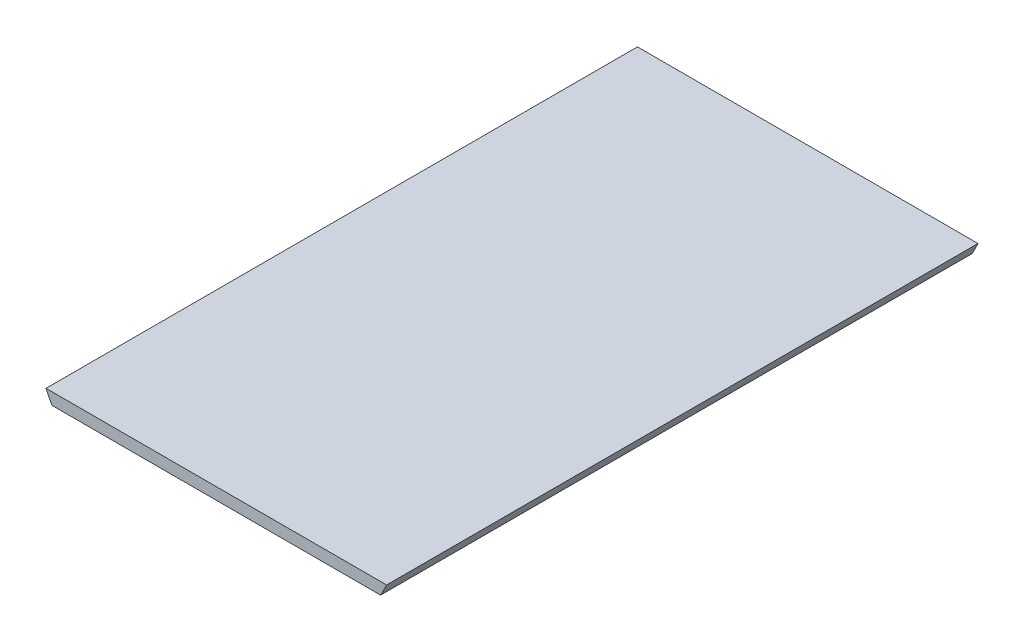
SolidWorks part; units mm, degrees
material "Brass"
ref_plane "Front Plane" through (0, 0, 0) normal (0, 0, 1) x (1, 0, 0)
ref_plane "Top Plane" through (0, 0, 0) normal (0, 1, 0) x (1, 0, 0)
ref_plane "Right Plane" through (0, 0, 0) normal (1, 0, 0) x (0, 0, -1)
sketch "Sketch2" plane through (0, 0, 0) normal (0, 0, 1) x (1, 0, 0)
  line L1 (0, -21.393) -> (0, -24.5934) construction
  line L2 (-44.45, -24.5934) -> (44.45, -24.5934)
  line L4 (-46.0758, -21.393) -> (46.0758, -21.393)
  arc A1 (-46.0758, -21.393) -> (-44.45, -24.5934) centre (0, 0) ccw
  arc A3 (44.45, -24.5934) -> (46.0758, -21.393) centre (0, 0) ccw
  dimension "D2" = 3.2004
extrude "Boss-Extrude1" add sketch "Sketch2" along normal blind 160.02 contours L4 A3 L2 A1
